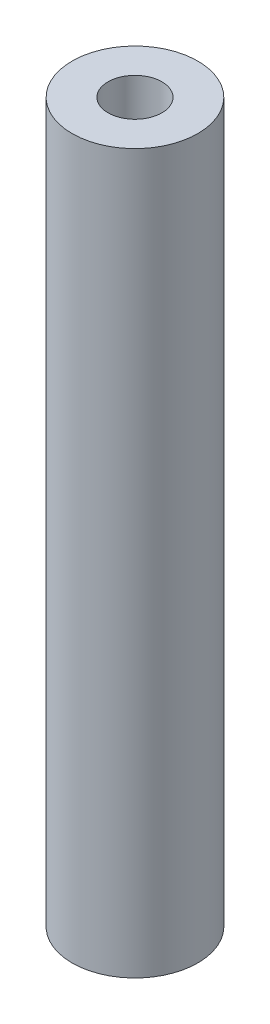
SolidWorks part; units mm, degrees
ref_plane "Front Plane" through (0, 0, 0) normal (0, 0, 1) x (1, 0, 0)
ref_plane "Top Plane" through (0, 0, 0) normal (0, 1, 0) x (1, 0, 0)
ref_plane "Right Plane" through (0, 0, 0) normal (1, 0, 0) x (0, 0, -1)
sketch "Sketch1" plane through (0, 0, 0) normal (0, 1, 0) x (1, 0, 0)
  circle A0 centre (0, 0) radius 3.5
  circle A1 centre (0, 0) radius 1.5
  dimension "D1" = 7
  dimension "D2" = 3
extrude "Boss-Extrude1" add sketch "Sketch1" along normal blind 40
